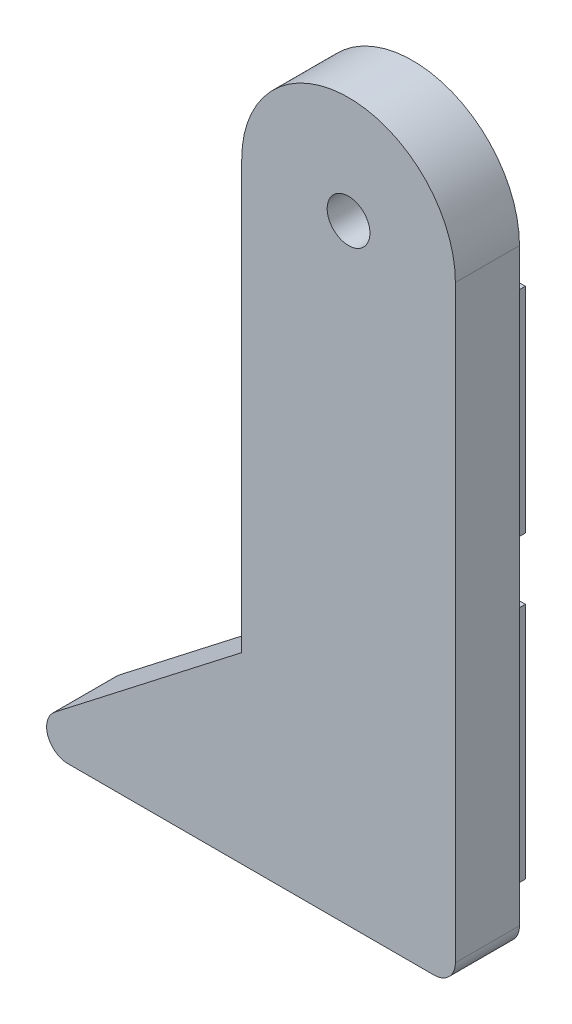
SolidWorks part; units mm, degrees
ref_plane "前视基准面" through (0, 0, 0) normal (0, 0, 1) x (1, 0, 0)
ref_plane "上视基准面" through (0, 0, 0) normal (0, 1, 0) x (1, 0, 0)
ref_plane "右视基准面" through (0, 0, 0) normal (1, 0, 0) x (0, 0, -1)
sketch "草图1" plane through (0, 0, 0) normal (0, 0, 1) x (1, 0, 0)
  line L0 (-5, 0) -> (-5, -20)
  line L1 (-5, -20) -> (5, -20)
  line L2 (5, -20) -> (5, 0)
  arc A0 (5, 0) -> (-5, 0) centre (0, 0) ccw
  circle A1 centre (0, 0) radius 1
  dimension "D1" = 10
  dimension "D2" = 2
extrude "凸台-拉伸1" add sketch "草图1" along normal blind 3
sketch "草图2" plane through (0, 0, 3) normal (0, 0, 1) x (1, 0, 0)
  line L0 (-5, -20) -> (5, -20)
  line L1 (5, -20) -> (5, -28.5715)
  line L2 (-5, -20) -> (-16.0533, -28.5715)
  line L3 (-16.0533, -28.5715) -> (5, -28.5715)
extrude "凸台-拉伸2" add sketch "草图2" against normal up to surface (3 mm away) up to face at (0, -8.75, 0)
fillet "圆角2" radius 1 1 edges at (-16.0533, -28.5715, 1.5)
fillet "圆角3" radius 1 1 edges at (5, -28.5715, 1.5)
sketch "草图3" plane through (0, 0, 3) normal (0, 0, 1) x (1, 0, 0)
  line L0 (-3.675, -2.5104) -> (-3.675, -12.5168)
  line L1 (-3.675, -12.5168) -> (-2.3499, -12.5168)
  line L2 (-2.3499, -12.5168) -> (-2.3499, -8.5417)
  line L3 (-2.3499, -8.5417) -> (2.4477, -12.5168)
  line L4 (2.4477, -12.5168) -> (4.2753, -12.5168)
  line L5 (4.2753, -12.5168) -> (-2.3499, -7.0273)
  line L6 (-2.3499, -7.0273) -> (4.2753, -2.5104)
  line L7 (4.2753, -2.5104) -> (1.3927, -2.5104)
  line L8 (1.3927, -2.5104) -> (-2.3499, -5.062)
  line L9 (-2.3499, -5.062) -> (-2.3499, -2.5104)
  line L10 (-2.3499, -2.5104) -> (-3.675, -2.5104)
  line L11 (-3.675, -15.0235) -> (-3.675, -26.5441)
  line L12 (-3.675, -26.5441) -> (-2.3499, -26.5441)
  line L13 (-2.3499, -26.5441) -> (-2.3499, -21.8379)
  line L14 (-2.3499, -21.8379) -> (2.3563, -26.5441)
  line L15 (2.3563, -26.5441) -> (4.2753, -26.5441)
  line L16 (4.2753, -26.5441) -> (-2.3499, -19.9188)
  line L17 (-2.3499, -19.9188) -> (4.2753, -15.4019)
  line L18 (4.2753, -15.4019) -> (1.3927, -15.4019)
  line L19 (1.3927, -15.4019) -> (-2.3499, -17.9535)
  line L20 (-2.3499, -17.9535) -> (-2.3499, -15.0235)
  line L21 (-2.3499, -15.0235) -> (-3.675, -15.0235)
sketch "草图4" plane through (0, 0, 0) normal (0, 0, -1) x (-1, 0, 0)
  line L0 (-4.2753, -2.5104) -> (-4.2753, -12.5168)
  line L1 (-4.2753, -12.5168) -> (-2.996, -12.5168)
  line L2 (-2.4477, -12.5168) -> (-4.2753, -12.5168) construction
  line L3 (-2.996, -12.5168) -> (-2.996, -8.633)
  line L4 (-2.996, -8.633) -> (1.9387, -12.5168)
  line L5 (1.9387, -12.5168) -> (4.3147, -12.5168)
  line L6 (4.3147, -12.5168) -> (-2.996, -6.7631)
  line L7 (-2.996, -6.7631) -> (4.3147, -2.5104)
  line L8 (4.3147, -2.5104) -> (1.2077, -2.5104)
  line L9 (1.2077, -2.5104) -> (-2.996, -4.9557)
  line L10 (-2.996, -4.9557) -> (-2.996, -2.5104)
  line L11 (-4.2753, -2.5104) -> (-1.3927, -2.5104) construction
  line L12 (-2.996, -2.5104) -> (-4.2753, -2.5104)
  line L13 (-4.2753, -15.4019) -> (-4.2753, -26.5441)
  line L14 (-4.2753, -26.5441) -> (-2.996, -26.5441)
  line L15 (-2.3563, -26.5441) -> (-4.2753, -26.5441) construction
  line L16 (-2.996, -26.5441) -> (-2.996, -22.6146)
  line L17 (-2.996, -22.6146) -> (1.9387, -26.5441)
  line L18 (1.9387, -26.5441) -> (4.3147, -26.5441)
  line L19 (4.3147, -26.5441) -> (-2.996, -20.7226)
  line L20 (-2.996, -20.7226) -> (4.3147, -15.4019)
  line L21 (4.3147, -15.4019) -> (1.2077, -15.4019)
  line L22 (1.2077, -15.4019) -> (-2.996, -18.4613)
  line L23 (-2.996, -18.4613) -> (-2.996, -15.4019)
  line L24 (-4.2753, -15.4019) -> (-1.3927, -15.4019) construction
  line L25 (-2.996, -15.4019) -> (-4.2753, -15.4019)
extrude "凸台-拉伸4" add sketch "草图4" along normal blind 1
